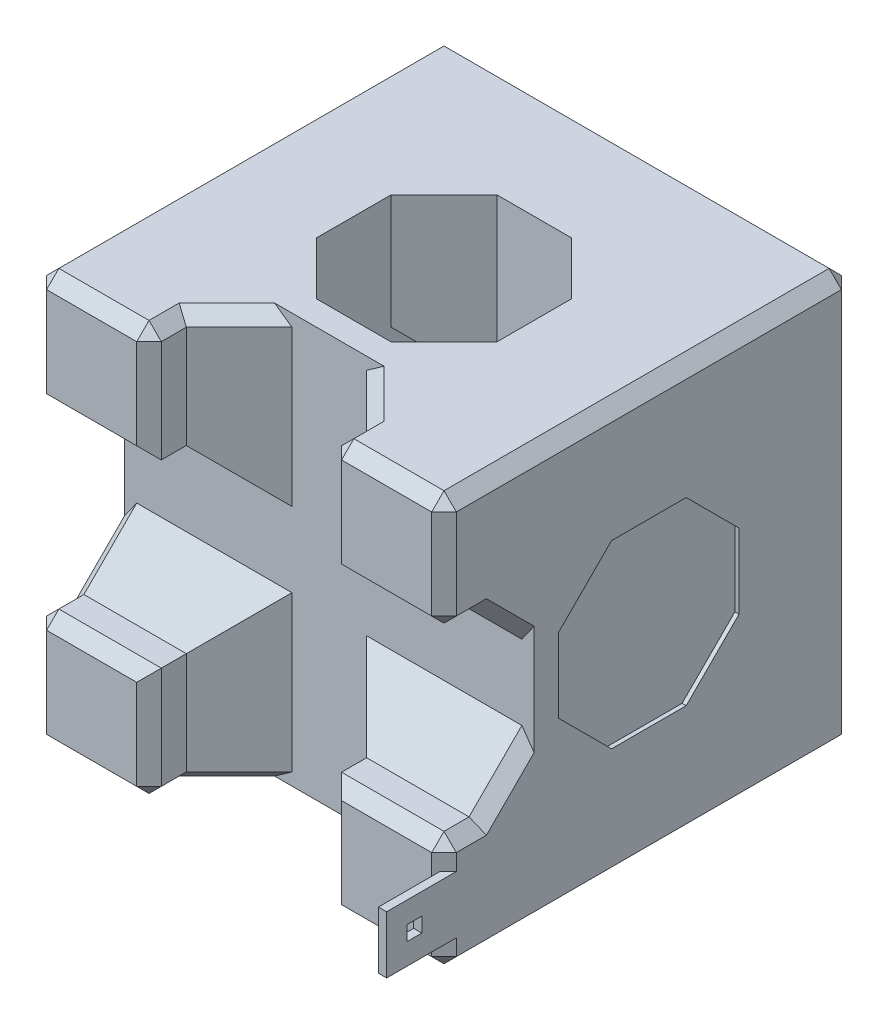
SolidWorks part; units mm, degrees
ref_plane "Front" through (0, 0, 0) normal (0, 0, 1) x (1, 0, 0)
ref_plane "Top" through (0, 0, 0) normal (0, 1, 0) x (1, 0, 0)
ref_plane "Right" through (0, 0, 0) normal (1, 0, 0) x (0, 0, -1)
sketch "Sketch1" plane through (0, 0, 0) normal (0, 0, 1) x (1, 0, 0)
  line L1 (0, 0) -> (50, 0)
  line L2 (0, 0) -> (0, 50)
  line L3 (0, 50) -> (50, 50)
  line L4 (50, 0) -> (50, 50)
  dimension "D1" = 50
extrude "Boss-Extrude1" add sketch "Sketch1" along normal blind 50
sketch "Sketch2" plane through (0, 0, 0) normal (-1, 0, 0) x (0, 0, 1)
  line L0 (25, 25) -> (25, 50) construction
  line L1 (50, 25) -> (25, 25) construction
  line L2 (50, 50) -> (50, 0) construction
  line L4 (45.4437, 14) -> (54.5563, 14)
  line L5 (54.5563, 14) -> (61, 20.4437)
  line L6 (61, 20.4437) -> (61, 29.5563)
  line L7 (50, 50) -> (0, 50) construction
  line L8 (61, 29.5563) -> (54.5563, 36)
  line L9 (54.5563, 36) -> (45.4437, 36)
  line L10 (14, 36) -> (36, 36) construction
  line L11 (14, 36) -> (14, 14) construction
  line L12 (14, 14) -> (36, 14) construction
  line L13 (36, 36) -> (36, 14) construction
  line L14 (36, 29.5563) -> (29.5563, 36)
  line L15 (14, 36) -> (36, 14) construction
  line L16 (29.5563, 36) -> (20.4437, 36)
  line L17 (14, 14) -> (36, 36) construction
  line L18 (45.4437, 36) -> (39, 29.5563)
  line L19 (39, 29.5563) -> (39, 20.4437)
  line L20 (39, 20.4437) -> (45.4437, 14)
  line L26 (20.4437, 36) -> (14, 29.5563)
  line L27 (14, 29.5563) -> (14, 20.4437)
  line L28 (14, 20.4437) -> (20.4437, 14)
  line L29 (20.4437, 14) -> (29.5563, 14)
  line L30 (29.5563, 14) -> (36, 20.4437)
  line L31 (36, 20.4437) -> (36, 29.5563)
  circle A0 centre (50, 25) radius 11 construction
  circle A1 centre (25, 25) radius 11 construction
  point P5 (25, 25)
  dimension "D1" = 22
extrude "Cut-Extrude1" cut sketch "Sketch2" against normal through all
sketch "Sketch10" plane through (0, 0, 0) normal (0, -1, 0) x (1, 0, 0)
  line L0 (0, 50) -> (50, 50) construction
  line L1 (29.5563, 36) -> (20.4437, 36)
  line L2 (20.4437, 36) -> (14, 29.5563)
  line L3 (14, 29.5563) -> (14, 20.4437)
  line L4 (14, 20.4437) -> (20.4437, 14)
  line L5 (20.4437, 14) -> (29.5563, 14)
  line L6 (29.5563, 14) -> (36, 20.4437)
  line L7 (36, 20.4437) -> (36, 29.5563)
  line L8 (36, 29.5563) -> (29.5563, 36)
  line L9 (29.5563, 39) -> (36, 45.4437)
  line L10 (36, 45.4437) -> (36, 54.5563)
  line L11 (36, 54.5563) -> (29.5563, 61)
  line L12 (29.5563, 61) -> (20.4437, 61)
  line L13 (20.4437, 61) -> (14, 54.5563)
  line L14 (14, 54.5563) -> (14, 45.4437)
  line L15 (14, 45.4437) -> (20.4437, 39)
  line L16 (20.4437, 39) -> (29.5563, 39)
  line L17 (0, 25) -> (25, 25) construction
  line L18 (0, 50) -> (0, 0) construction
  circle A0 centre (25, 25) radius 11 construction
  circle A1 centre (25, 50) radius 11 construction
  dimension "D1" = 22
extrude "Cut-Extrude2" cut sketch "Sketch10" against normal through all
chamfer "Chamfer1" distance 1.5 angle 45 40 edges at (50, 17.2218, 42.2218) (50, 14, 47.7218) (17.2218, 50, 42.2218) (14, 50, 47.7218) (25, 50, 0) (50, 32.7782, 42.2218) (50, 36, 47.7218) (32.7782, 50, 42.2218) (36, 50, 47.7218) (36, 43, 50) (43, 36, 50) (50, 43, 50) (50, 50, 25) (50, 25, 0) (0, 17.2218, 42.2218) (0, 14, 47.7218) (7, 14, 50) (0, 7, 50) (14, 7, 50) (17.2218, 0, 42.2218) (14, 0, 47.7218) (7, 0, 50) (0, 0, 25) (50, 7, 50) (43, 14, 50) (36, 7, 50) (32.7782, 0, 42.2218) (36, 0, 47.7218) (43, 0, 50) (50, 0, 25) (25, 0, 0) (0, 25, 0) (0, 50, 25) (0, 43, 50) (0, 32.7782, 42.2218) (0, 36, 47.7218) (7, 36, 50) (14, 43, 50) (7, 50, 50) (43, 50, 50)
sketch "Sketch11" plane through (0, 0, 14) normal (0, 0, 1) x (1, 0, 0)
  line L0 (50, 36) -> (36, 36) construction
  line L1 (36.5, 36) -> (36, 36)
  line L2 (36.5, 36) -> (36.5, 14)
  line L3 (36.5, 14) -> (36, 14)
  line L4 (36, 36) -> (36, 14)
  line L5 (13.5, 36) -> (14, 36)
  line L6 (13.5, 36) -> (13.5, 14)
  line L7 (13.5, 14) -> (14, 14)
  line L8 (14, 36) -> (14, 14)
  line L9 (50, 14) -> (36, 14) construction
  line L10 (36, 14) -> (36, 0) construction
  line L11 (14, 14) -> (14, 0) construction
  line L12 (48.5, 36) -> (36, 36) construction
  line L13 (49, 36) -> (49.5, 36)
  line L14 (49, 36) -> (49, 14)
  line L15 (49, 14) -> (49.5, 14)
  line L16 (49.5, 36) -> (49.5, 14)
  line L17 (14, 36) -> (1.5, 36) construction
  line L18 (1, 36) -> (0.5, 36)
  line L19 (1, 36) -> (1, 14)
  line L20 (1, 14) -> (0.5, 14)
  line L21 (0.5, 36) -> (0.5, 14)
  line L22 (50, 29.5563) -> (50, 20.4437) construction
  line L23 (0, 29.5563) -> (0, 20.4437) construction
  line L24 (14, 14) -> (0, 14) construction
  dimension "D1" = 0.5
  dimension "D2" = 0.5
  dimension "D3" = 0.5
extrude "Boss-Extrude2" add sketch "Sketch11" along normal up to surface (25 mm away) up to face at (25, 25, 39)
sketch "Sketch12" plane through (0, 0, 50) normal (0, 0, 1) x (1, 0, 0)
  line L0 (50, 12.5) -> (50, 1.5) construction
  line L1 (50, 10.5) -> (49, 10.5)
  line L2 (50, 10.5) -> (50, 3.5)
  line L3 (50, 3.5) -> (49, 3.5)
  line L4 (49, 10.5) -> (49, 3.5)
  point P6 (50, 7)
  dimension "D1" = 7
  dimension "D2" = 1
extrude "Boss-Extrude3" add sketch "Sketch12" along normal blind 7 and the other way blind 10
sketch "Sketch13" plane through (50, 0, 0) normal (1, 0, 0) x (0, 0, -1)
  line L0 (-57, 7) -> (-54.5, 7) construction
  line L1 (-54.5, 6.1) -> (-52.7, 6.1)
  line L2 (-54.5, 6.1) -> (-54.5, 7.9)
  line L3 (-54.5, 7.9) -> (-52.7, 7.9)
  line L4 (-52.7, 6.1) -> (-52.7, 7.9)
  line L5 (-57, 3.5) -> (-57, 10.5) construction
  dimension "D1" = 2.5
  dimension "D2" = 1.8
extrude "Cut-Extrude3" cut sketch "Sketch13" against normal blind 7
